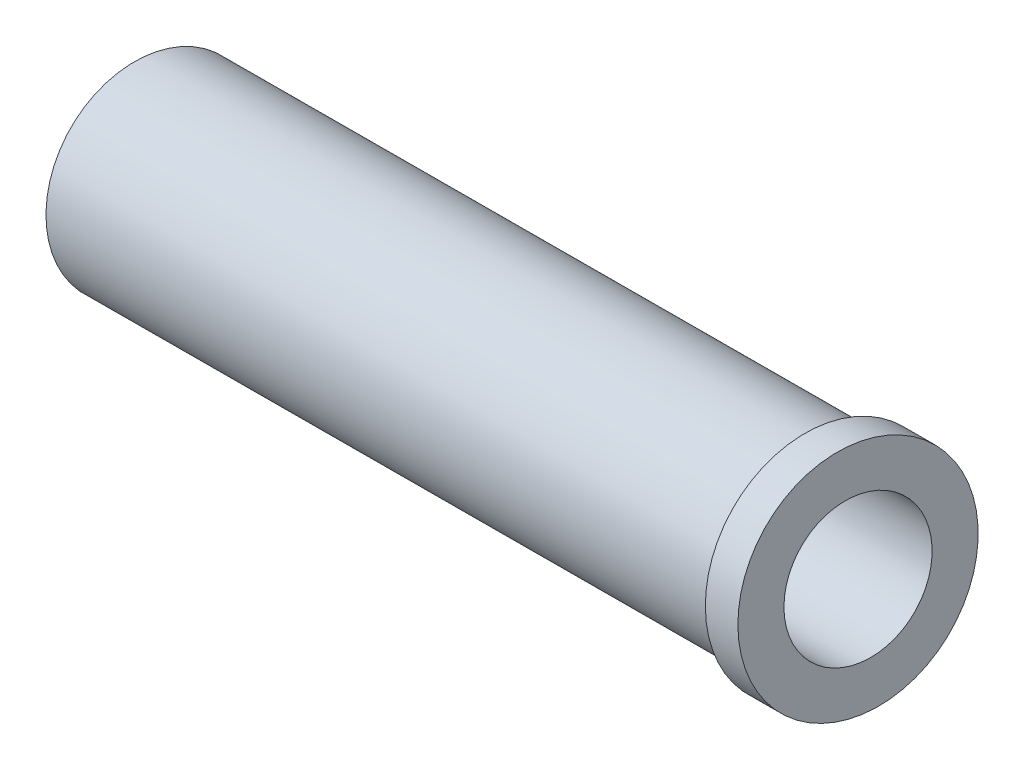
SolidWorks part; units mm, degrees
material "Caucho"
ref_plane "Alzado" through (0, 0, 0) normal (0, 0, 1) x (1, 0, 0)
ref_plane "Planta" through (0, 0, 0) normal (0, 1, 0) x (1, 0, 0)
ref_plane "Vista lateral" through (0, 0, 0) normal (1, 0, 0) x (0, 0, -1)
sketch3d "Sk_Puno"
  line L0 (250.774, 39.9286, -26.4554) -> (379.4801, 26.798, -39.196)
  dimension "D1" = 130
sweep "Puno" add path "Sk_Puno" circular profile diameter 32 parameters "D3"=32
sketch3d "Sk_Collarin"
  line L0 (250.774, 39.9286, -26.4554) -> (256.7143, 39.3226, -27.0434)
  dimension "D1" = 6
sweep "Collarin" add path "Sk_Collarin" circular profile diameter 36 parameters "D3"=36
sketch3d "Sk_Agujero_puno"
  line L0 (249.7839, 40.0296, -26.3574) -> (377.5, 27, -39)
  dimension "D1" = 129
sweep "Agujero_puno" cut path "Sk_Agujero_puno" circular profile diameter 22.2 parameters "D3"=22.2
mirror "Simetria_lado_izq" about plane through (0, 0, 0) normal (1, 0, 0) of bodies 103
delete or keep bodies "Borrar_original_dcho" type delete bodies bodies 103
